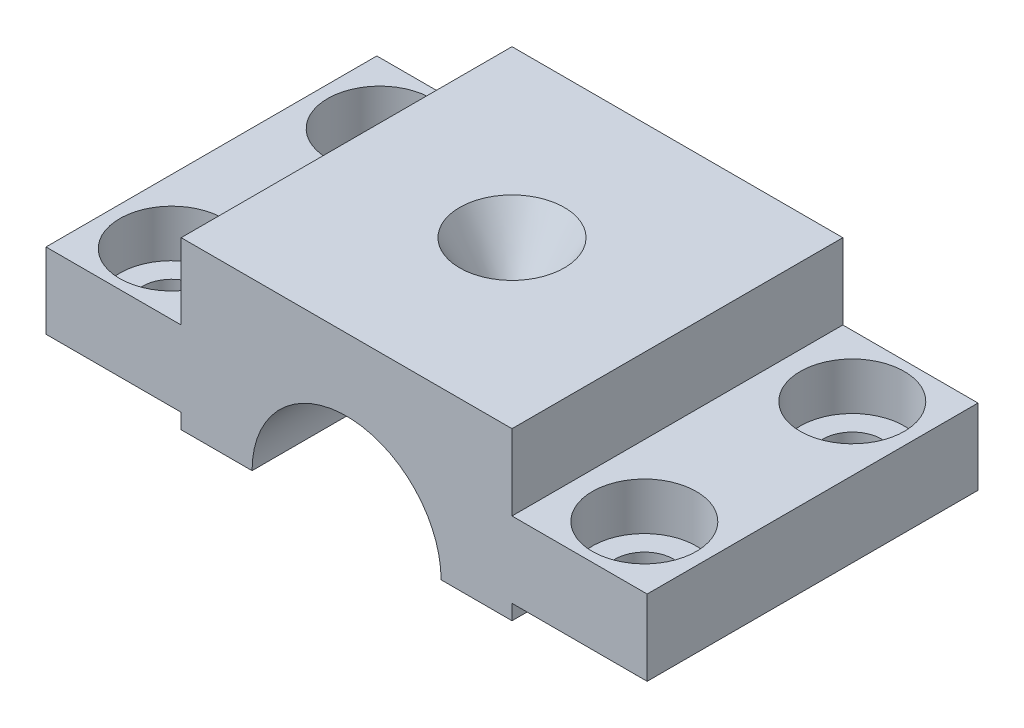
SolidWorks part; units mm, degrees
material "Brąz cynowy łożyskowy"
ref_plane "Płaszczyzna przednia" through (0, 0, 0) normal (0, 0, 1) x (1, 0, 0)
ref_plane "Płaszczyzna górna" through (0, 0, 0) normal (0, 1, 0) x (1, 0, 0)
ref_plane "Płaszczyzna prawa" through (0, 0, 0) normal (1, 0, 0) x (0, 0, -1)
sketch "Szkic1" plane through (0, 0, 0) normal (0, 0, 1) x (1, 0, 0)
  line L1 (-15.9, 0) -> (15.9, 0)
  line L2 (-15.9, 0) -> (-15.9, 8.8)
  line L3 (-15.9, 8.8) -> (15.9, 8.8)
  line L4 (15.9, 0) -> (15.9, 8.8)
  point P4 (0, 0)
  dimension "D1" = 8.8
  dimension "D2" = 31.8
extrude "Dodanie-wyciągnięcie1" add sketch "Szkic1" along normal mid plane 17.5
sketch "Szkic2" plane through (0, 0, 0) normal (0, -1, 0) x (1, 0, 0)
  line L0 (-15.9, -8.75) -> (15.9, -8.75) construction
  line L1 (15.9, 8.75) -> (8.75, 8.75)
  line L2 (15.9, 8.75) -> (15.9, -8.75)
  line L3 (15.9, -8.75) -> (8.75, -8.75)
  line L4 (8.75, 8.75) -> (8.75, -8.75)
  dimension "D1" = 7.15
extrude "Wytnij-wyciągnięcie1" cut sketch "Szkic2" against normal blind 0.8
sketch "Szkic3" plane through (0, 0, 8.75) normal (0, 0, 1) x (1, 0, 0)
  line L0 (15.9, 8.8) -> (-15.9, 8.8) construction
  line L1 (8.75, 8.8) -> (15.9, 8.8)
  line L2 (8.75, 8.8) -> (8.75, 4.8)
  line L3 (8.75, 4.8) -> (15.9, 4.8)
  line L4 (15.9, 8.8) -> (15.9, 4.8)
  line L5 (15.9, 0.8) -> (15.9, 8.8) construction
  line L6 (8.75, 0.8) -> (8.75, 0) construction
  point P10 (0, 0)
  dimension "D1" = 4
extrude "Wytnij-wyciągnięcie2" cut sketch "Szkic3" against normal through all
hole_wizard "Pogłębienie walcowe pod M2.5 Śrubę z łbem walcowym z gniazdem1" positions "Szkic4" profile "Szkic5" counterbore size "M2.5" standard "Ansi Metric" end condition through all
sketch "Szkic4" plane through (0, 4.8, 0) normal (0, 1, 0) x (1, 0, 0)
  line L0 (12.5, 5.5) -> (12.5, -5.5)
  point P0 (12.5, 5.5)
  point P2 (12.5, -5.5)
  dimension "D1" = 12.5
  dimension "D2" = 5.5
  dimension "D3" = 11
sketch "Szkic5" plane through (12.5, 4.8, -5.5) normal (1, 0, 0) x (0, 0, 1)
  line L0 (0, 0) -> (0, 4.8)
  line L1 (0, 4.8) -> (1.55, 4.8)
  line L3 (1.55, 4.8) -> (1.55, 2.5)
  line L4 (1.55, 2.5) -> (2.75, 2.5)
  line L5 (2.75, 2.5) -> (2.75, 0)
  line L7 (2.75, 0) -> (0, 0)
  line L11 (0, -6.35) -> (0, 107.95) construction
  dimension "Średnica otworu na wylot" = 3.1
  dimension "Głębokość otworu na wylot" = 4.8
  dimension "Średnica pogłębienia walcowego" = 5.5
  dimension "Głębokość pogłębienia walcowego" = 2.5
mirror "Lustro1" about plane through (0, 0, 0) normal (1, 0, 0) of "Pogłębienie walcowe pod M2.5 Śrubę z łbem walcowym z gniazdem1", "Wytnij-wyciągnięcie2", "Wytnij-wyciągnięcie1"
sketch "Szkic6" plane through (0, 0, 8.75) normal (0, 0, 1) x (1, 0, 0)
  circle A0 centre (0, 0) radius 5
  dimension "D1" = 10
extrude "Wytnij-wyciągnięcie3" cut sketch "Szkic6" against normal through all
sketch "Szkic7" plane through (0, 0, 0) normal (0, 0, 1) x (1, 0, 0)
  line L0 (0, 0) -> (0, 3) construction
  line L4 (0, 0) -> (0, 8.8)
  line L5 (8.75, 8.8) -> (-8.75, 8.8) construction
  line L6 (0, 8.8) -> (2.7707, 8.8)
  line L7 (2.7707, 8.8) -> (0.75, 5.3)
  line L8 (0.75, 5.3) -> (0.75, 0)
  line L9 (0.75, 0) -> (0, 0)
  dimension "D1" = 1.5
  dimension "D2" = 3.5
  dimension "D3" = 30
revolve "Wycięcie-obrót5" cut sketch "Szkic7" angle 360 about L0
equation "\"D1@Szkic2\"=(31.8-17.5)/2"
